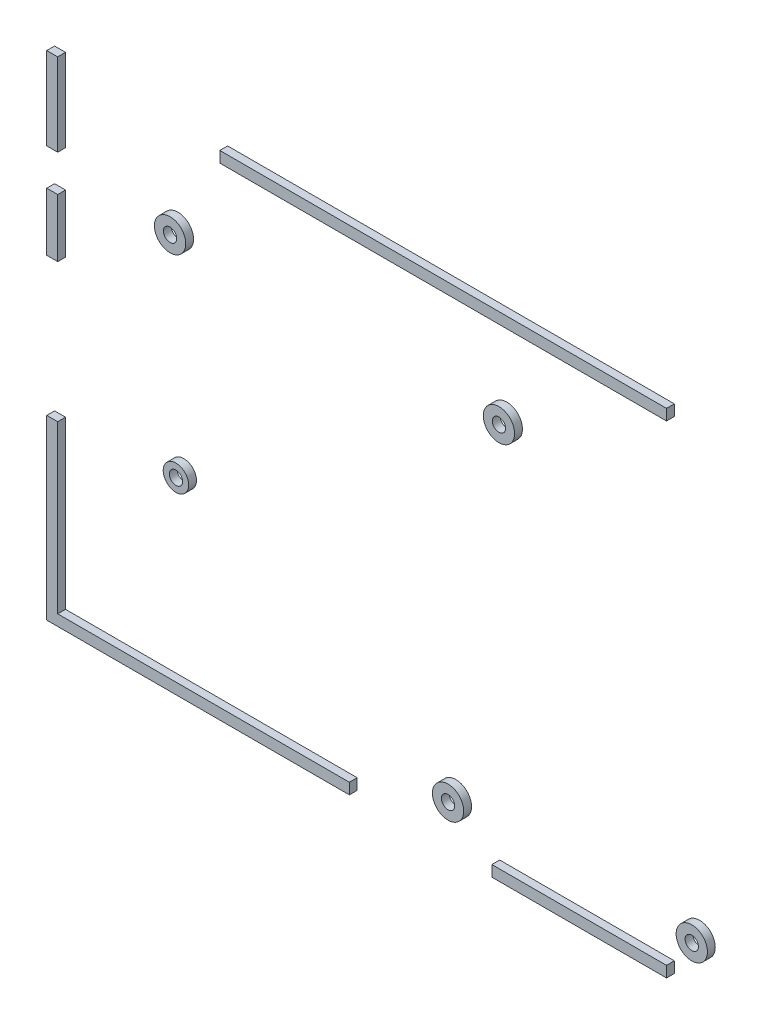
SolidWorks part; units mm, degrees
material "Custom Plastic"
ref_plane "Front Plane" through (0, 0, 0) normal (0, 0, 1) x (1, 0, 0)
ref_plane "Top Plane" through (0, 0, 0) normal (0, 1, 0) x (1, 0, 0)
ref_plane "Right Plane" through (0, 0, 0) normal (1, 0, 0) x (0, 0, -1)
sketch "Sketch1" plane through (0, 0, 0) normal (0, 0, 1) x (1, 0, 0)
  line L0 (-176, 32.55) -> (-176, -63) construction
  line L1 (-173.2, 41.9) -> (-176, 41.9)
  line L2 (-173.2, 41.9) -> (-173.2, 63)
  line L3 (-173.2, 63) -> (-176, 63)
  line L4 (-176, 41.9) -> (-176, 63)
  line L5 (-176, 32.55) -> (-173.2, 32.55)
  line L6 (-176, 32.55) -> (-176, 17.7)
  line L7 (-176, 17.7) -> (-173.2, 17.7)
  line L8 (-173.2, 32.55) -> (-173.2, 17.7)
  line L9 (-173.2, -17.7) -> (-176, -17.7)
  line L10 (-173.2, -17.7) -> (-173.2, -60.2)
  line L11 (-173.2, -60.2) -> (-176, -60.2)
  line L12 (-176, -17.7) -> (-176, -60.2)
  line L13 (-17.7, -63.2) -> (-17.7, -60.2) construction
  line L14 (-176, -63) -> (-98.7, -63)
  line L15 (-176, -63) -> (-176, -60.2)
  line L16 (-176, -60.2) -> (-98.7, -60.2)
  line L17 (-98.7, -63) -> (-98.7, -60.2)
  line L18 (-62.3, -60.2) -> (-17.7, -60.2)
  line L19 (-62.3, -60.2) -> (-62.3, -63)
  line L20 (-62.3, -63) -> (-17.7, -63)
  line L21 (-17.7, -60.2) -> (-17.7, -63)
  line L22 (-176, -63) -> (176, -63) construction
  line L23 (176, 63) -> (-176, 63) construction
  line L24 (-131.8, 60.2) -> (-17.7, 60.2)
  line L25 (-131.8, 60.2) -> (-131.8, 63)
  line L26 (-131.8, 63) -> (-17.7, 63)
  line L27 (-17.7, 60.2) -> (-17.7, 63)
  line L28 (-17.7, 63.2) -> (-17.7, 60.2) construction
  circle A0 centre (-144.5, 38) radius 4
  circle A1 centre (-144.5, 38) radius 1.7
  circle A2 centre (-144.5, 38) radius 4 construction
  circle A3 centre (-60.5, 38) radius 4
  circle A4 centre (-60.5, 38) radius 4 construction
  circle A5 centre (-60.5, 38) radius 1.7
  circle A6 centre (-143, -15) radius 3.25
  circle A7 centre (-143, -15) radius 3.25 construction
  circle A8 centre (-143, -15) radius 1.7
  circle A9 centre (-73.5, -52) radius 4
  circle A10 centre (-73.5, -52) radius 4 construction
  circle A11 centre (-73.5, -52) radius 1.7
  circle A12 centre (-11.25, -52) radius 4
  circle A13 centre (-11.25, -52) radius 4 construction
  circle A14 centre (-11.25, -52) radius 1.7
  dimension "D1" = 3.4
  dimension "D2" = 3.4
  dimension "D3" = 3.4
  dimension "D4" = 3.4
  dimension "D5" = 3.4
extrude "Boss-Extrude1" add sketch "Sketch1" along normal up to surface (2 mm away) contours L24 L27 L26 L25 | A3 A5 | A0 A1 | L4 L1 L2 L3 | L8 L5 L6 L7 | L9 L12 L11 L10 | L14 L17 L16 L11 L15 | A6 A8 | L21 L18 L19 L20 | A9 A11 | A12 A14
